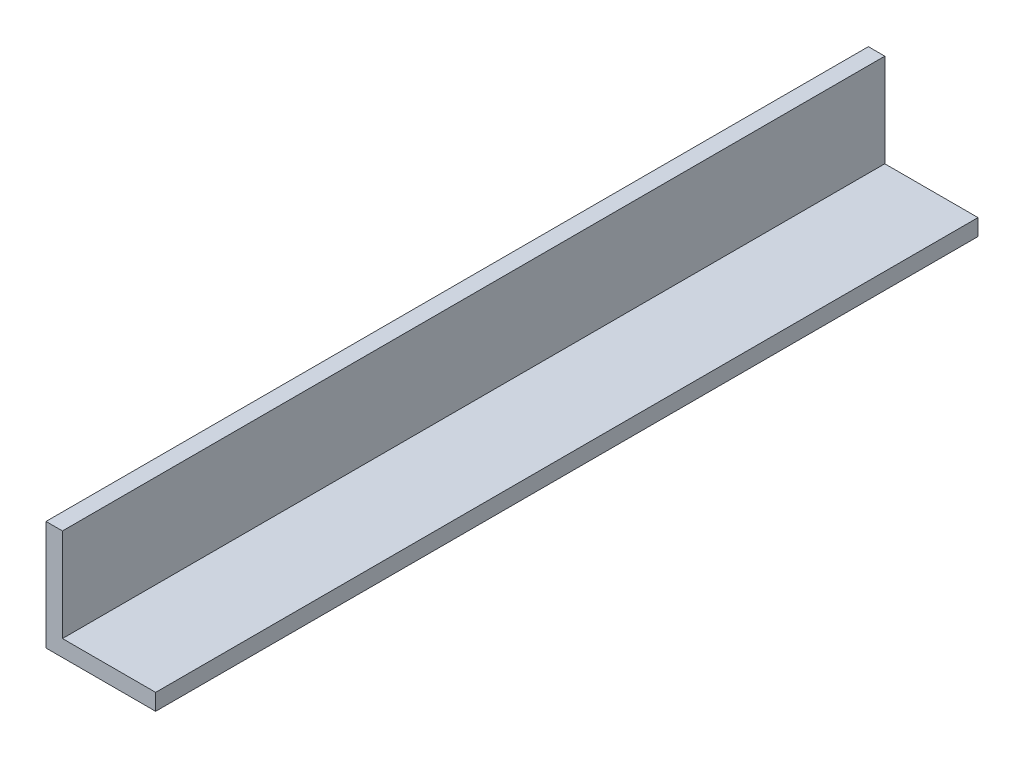
SolidWorks part; units mm, degrees
ref_plane "Front Plane" through (0, 0, 0) normal (0, 0, 1) x (1, 0, 0)
ref_plane "Top Plane" through (0, 0, 0) normal (0, 1, 0) x (1, 0, 0)
ref_plane "Right Plane" through (0, 0, 0) normal (1, 0, 0) x (0, 0, -1)
sketch "Sketch1" plane through (0, 0, 0) normal (0, 0, 1) x (1, 0, 0)
  line L0 (0, 0) -> (20, 0)
  line L1 (20, 0) -> (20, 3)
  line L2 (20, 3) -> (3, 3)
  line L3 (0, 0) -> (0, 20)
  line L4 (0, 20) -> (3, 20)
  line L5 (3, 20) -> (3, 3)
  point P0 (3, 3.3527)
  point P3 (0, 0)
  point P7 (1.1, 2.0971)
  point P9 (0.2059, 0)
  dimension "D1" = 3
  dimension "D2" = 3
  dimension "D3" = 20
  dimension "D4" = 20
extrude "Boss-Extrude1" add sketch "Sketch1" along normal blind 150
